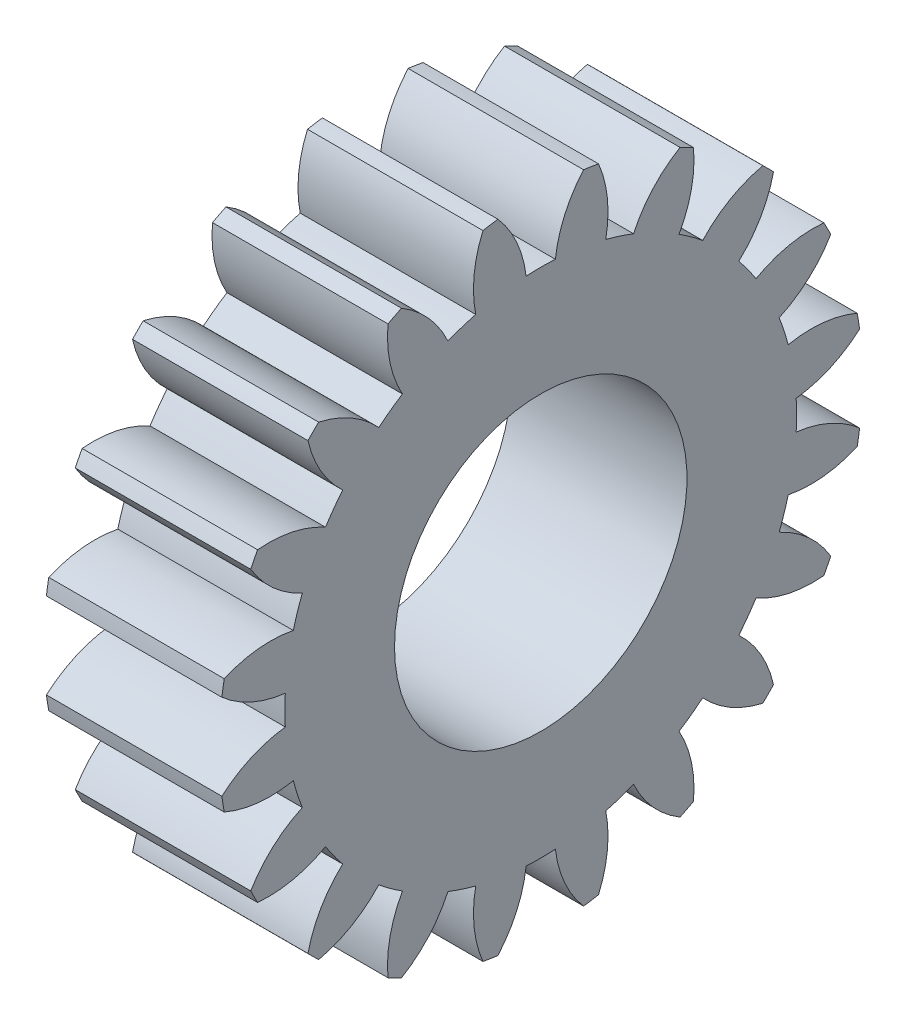
SolidWorks part; units mm, degrees
ref_plane "Plane1" through (0, 0, 0) normal (0, 0, 1) x (1, 0, 0)
ref_plane "Plane2" through (0, 0, 0) normal (0, 1, 0) x (1, 0, 0)
ref_plane "Plane3" through (0, 0, 0) normal (1, 0, 0) x (0, 0, -1)
sketch "HoldingSke" plane through (0, 0, 0) normal (0, 1, 0) x (1, 0, 0)
  line L0 (0, 0) -> (1.8794, -0.684)
  line L1 (-15, 0) -> (100, 0) construction
  line L2 (0, 0) -> (-2.1039, 2.3779)
  line L3 (0, 0) -> (-11.863, 4.5341)
  line L4 (0, 0) -> (8.1152, 2.9537)
  line L5 (0, 0) -> (-46.8476, -17.4728)
  line L6 (0, 0) -> (-2.4869, -1.6779)
  line L7 (-2.1039, 2.3779) -> (8.6586, 51.2059)
  line L8 (-76.2, 54.61) -> (-75.3, 54.61)
  line L9 (-71.009, 38.7566) -> (-53.1078, 45.2721)
  line L10 (-76.2, 71.12) -> (104.1128, 71.12)
  line L11 (0, 0) -> (-3, 0)
  line L12 (-76.2, 101.6) -> (-76.181, 101.6)
  line L13 (24.9733, 27.94) -> (52.9518, 28.4284)
  line L14 (24.9733, 27.94) -> (24.9743, 27.94)
  line L15 (24.9733, 27.94) -> (100.4006, 29.5858)
  line L16 (-63.627, -0.5) -> (-12.827, -0.5)
  circle A0 centre (0, 0) radius 2.5
  circle A1 centre (0, 0) radius 4.374
  circle A2 centre (0, 0) radius 37.5
  circle A3 centre (0, 0) radius 2.5
  dimension "MHD" = 8.748
  dimension "Hub_dia" = 75
  dimension "Bore" = 5
  dimension "MBD" = 5
  dimension "Num_teeth" = 20
  dimension "Pitch" = 2
  dimension "Overall_len" = 50
  dimension "Show_teeth" = 20
  dimension "Thickness" = 3
  dimension "OAL" = 50.0001
  dimension "T_dim" = 0.9
  dimension "Ap" = 20
  dimension "H" = 19.05
  dimension "Pitch_radius" = 180.3128
  dimension "Width" = 3
  dimension "Backlash" = 0.019
  dimension "Addendum_fac" = 1
  dimension "Dedendum_fac" = 1.25
  dimension "Clearance_fac" = 0.25
  dimension "Dedendum_add" = 0.001
  dimension "Module" = 0.5
sketch "BasProSke" plane through (0, 0, 0) normal (0, 1, 0) x (1, 0, 0)
  line L0 (-10, 0) -> (60, 0) construction
  line L1 (0, 0) -> (0, 5.5)
  line L2 (0, 0) -> (3, 0)
  line L3 (3, 0) -> (3, 5.5)
  line L4 (3, 5.5) -> (0, 5.5)
  dimension "Thickness" = 3
  dimension "Diameter" = 11
revolve "Base-Revolve" add sketch "BasProSke" angle 360 about L0
sketch "TooCutSke" plane through (0, 0, 0) normal (1, 0, 0) x (0, 0, -1)
  line L1 (0, 0) -> (0, 107) construction
  line L2 (0, 0) -> (-0.4255, 4.9819) construction
  line L3 (0, 0) -> (-1.5603, 9.8514) construction
  line L4 (-0.4255, 4.9819) -> (-0.7802, 4.9257) construction
  arc A0 (0.2499, 4.3669) -> (-0.2499, 4.3669) centre (0, 0) ccw
  arc A1 (0.7528, 5.4739) -> (-0.7528, 5.4739) centre (0, 0) ccw
  circle A2 centre (0, 0) radius 5 construction
  circle A3 centre (0, 0) radius 4.6985 construction
  arc A4 (-0.2499, 4.3669) -> (-0.7528, 5.4739) centre (-2.2361, 4.1322) ccw
  arc A5 (0.7528, 5.4739) -> (0.2499, 4.3669) centre (2.2361, 4.1322) ccw
  dimension "Root_dia" = 8.748
  dimension "Overcut_dia" = 11.0508
  dimension "Pitch_dia" = 10
  dimension "Base_dia" = 9.3969
  dimension "Flank_rad" = 2
  dimension "Half_ang" = 9
  dimension "Half_CT" = 0.359
extrude "ToothCut" cut sketch "TooCutSke" along normal through all
fillet "Breaks" [suppressed] radius 0.01
fillet "RootFillets" [suppressed] radius 0.126
pattern_circular "TeethCuts" count 20 every 18 about axis through (-10, 0, 0) along (1, 0, 0) of "ToothCut", "RootFillets", "Breaks"
sketch "HubNeaOneSke" plane through (0, 0, 0) normal (-1, 0, 0) x (0, 0, 1)
  circle A0 centre (0, 0) radius 4.374
  dimension "Diameter" = 8.748
extrude "HubNearOne" [suppressed] add sketch "HubNeaOneSke" along normal blind 47.0001
sketch "HubNeaBotSke" plane through (0, 0, 0) normal (-1, 0, 0) x (0, 0, 1)
  circle A0 centre (0, 0) radius 4.374
  dimension "Diameter" = 8.748
extrude "HubNearBoth" [suppressed] add sketch "HubNeaBotSke" along normal blind 23.5
ref_plane "FarPln" through (3, 0, 0) normal (1, 0, 0) x (0, 0, -1)
sketch "HubFarSke" plane through (3, 0, 0) normal (1, 0, 0) x (0, 0, -1)
  circle A0 centre (0, 0) radius 4.374
  dimension "Diameter" = 8.748
extrude "HubFar" [suppressed] add sketch "HubFarSke" along normal blind 23.5
sketch "BorSke" plane through (0, 0, 0) normal (1, 0, 0) x (0, 0, -1)
  circle A0 centre (0, 0) radius 2.5
  dimension "Diameter" = 5
extrude "Bore" cut sketch "BorSke" along normal mid plane 100.0001
sketch "KeySke" plane through (0, 0, 0) normal (1, 0, 0) x (0, 0, -1)
  line L0 (-1, 0) -> (-1, 3.4)
  line L1 (-1, 3.4) -> (1, 3.4)
  line L2 (1, 3.4) -> (1, 0)
  line L3 (0, 0) -> (0, 34) construction
  line L4 (-1, 0) -> (1, 0)
  dimension "Offset" = 3.4
  dimension "Width" = 2
extrude "Keyway" [suppressed] cut sketch "KeySke" along normal mid plane 100.0001
pattern_circular "Keyway2" [suppressed] count 2 every 90 about axis through (-10, 0, 0) along (1, 0, 0)
sketch "Croquis1" plane through (3, 0, 0) normal (1, 0, 0) x (0, 0, -1)
  line L0 (0, 2.5) -> (0, -2.5)
  line L1 (0, 0) -> (2.5, 0)
  circle A0 centre (0, 0) radius 2.5 construction
  circle A1 centre (0, 0) radius 5
  dimension "D1" = 10
equation "' \"Module@HoldingSke\" = 6.35"
equation "' \"Num_teeth@HoldingSke\" = 12"
equation "' \"Ap@HoldingSke\" =  20"
equation "' \"Ap@HoldingSke\" = 20"
equation "' \"Width@HoldingSke\" = 0.5 * 25.4"
equation "' \"Hub_dia@HoldingSke\"= 1 * 25.4"
equation "' \"Hub_dia@HoldingSke\" = 1 * 25.4"
equation "' \"Overall_len@HoldingSke\" = 1.0 * 25.4"
equation "' \"Bore@HoldingSke\" = 0.75 * 25.4"
equation "' \"T_dim@HoldingSke\" = 0.1 * 25.4"
equation "' \"Width@KeySke\" = 0.25 * 25.4"
equation "' \"Show_teeth@HoldingSke\" = 13"
equation "' \"Backlash@HoldingSke\" = 0.009 * 25.4"
equation "' \"Addendum_fac@HoldingSke\" = 1.0"
equation "' \"Dedendum_fac@HoldingSke\" = 1.25"
equation "' \"Dedendum_add@HoldingSke\" = 0.00005 * 25.4"
equation "' \"Clearance_fac@HoldingSke\" = 0.25"
equation "\"Pitch@HoldingSke\" = 1 / \"Module@HoldingSke\""
equation "\"Overcut_dia@TooCutSke\" = (\"Num_teeth@HoldingSke\" + 2 * \"Addendum_fac@HoldingSke\") / \"Pitch@HoldingSke\" + 0.002 * 25.4"
equation "\"Pitch_dia@TooCutSke\" = \"Num_teeth@HoldingSke\" / \"Pitch@HoldingSke\""
equation "\"Base_dia@TooCutSke\" = \"Num_teeth@HoldingSke\" / \"Pitch@HoldingSke\" * cos((\"Ap@HoldingSke\"  * 3.14159265 / 180))"
equation "\"Root_dia@TooCutSke\" = (\"Num_teeth@HoldingSke\" + 2) / \"Pitch@HoldingSke\" - 2 * (\"Addendum_fac@HoldingSke\" + \"Dedendum_fac@HoldingSke\") / \"Pitch@HoldingSke\" - \"Dedendum_add@HoldingSke\" * 2"
equation "\"Half_ang@TooCutSke\" = 180 / \"Num_teeth@HoldingSke\""
equation "\"Half_CT@TooCutSke\" = \"Num_teeth@HoldingSke\" / \"Pitch@HoldingSke\" * sin((3.14159265 / 2 / \"Num_teeth@HoldingSke\")) / 2 - 7 * \"Backlash@HoldingSke\" / 4"
equation "\"Flank_rad@TooCutSke\" = \"Num_teeth@HoldingSke\" / \"Pitch@HoldingSke\" / 5"
equation "\"Radius@RootFillets\" = \"Clearance_fac@HoldingSke\" / \"Pitch@HoldingSke\" + \"Dedendum_add@HoldingSke\""
equation "\"Break_rad@Breaks\" = 0.02 / \"Pitch@HoldingSke\""
equation "\"Thickness@HoldingSke\" = \"Width@HoldingSke\""
equation "\"OAL@HoldingSke\" = \"Thickness@HoldingSke\""
equation "\"MHD@HoldingSke\" = (\"Num_teeth@HoldingSke\" + 2) / \"Pitch@HoldingSke\" - 2 * (\"Addendum_fac@HoldingSke\" + \"Dedendum_fac@HoldingSke\")  / \"Pitch@HoldingSke\" - \"Dedendum_add@HoldingSke\" * 2"
equation "\"MBD@HoldingSke\" = (\"Num_teeth@HoldingSke\" + 2) / \"Pitch@HoldingSke\" - 2 * (\"Addendum_fac@HoldingSke\" + \"Dedendum_fac@HoldingSke\")  / \"Pitch@HoldingSke\" - \"Dedendum_add@HoldingSke\" * 2 - 0.002 * 25.4"
equation "\"MHD@HoldingSke\" = ((sgn( \"MHD@HoldingSke\" - \"Hub_dia@HoldingSke\" )-1)*( \"MHD@HoldingSke\" - \"Hub_dia@HoldingSke\" ))/-2+ \"Hub_dia@HoldingSke\""
equation "\"MBD@HoldingSke\" = ((sgn( \"MBD@HoldingSke\" - \"Bore@HoldingSke\" )-1)*( \"MBD@HoldingSke\" - \"Bore@HoldingSke\" ))/-2+ \"Bore@HoldingSke\""
equation "\"OAL@HoldingSke\" = ((sgn( \"OAL@HoldingSke\" - \"Overall_len@HoldingSke\" )+1)*( \"OAL@HoldingSke\" - \"Overall_len@HoldingSke\" ))/2 + \"Overall_len@HoldingSke\" + 0.000002 * 25.4"
equation "\"Num_teeth@TeethCuts\" = int( \"Show_teeth@HoldingSke\" ) + 1"
equation "\"Num_teeth@TeethCuts\" = ((sgn( \"Num_teeth@TeethCuts\" - \"Num_teeth@HoldingSke\" )-1)*( \"Num_teeth@TeethCuts\" - \"Num_teeth@HoldingSke\" ))/-2+ \"Num_teeth@HoldingSke\""
equation "\"Num_teeth@TeethCuts\" = ((sgn( \"Num_teeth@TeethCuts\" - 2.0)+1)*( \"Num_teeth@TeethCuts\" - 2.0))/2 +2.0"
equation "\"Angle@TeethCuts\" = 360.0 / \"Num_teeth@HoldingSke\""
equation "\"Diameter@BasProSke\" = (\"Num_teeth@HoldingSke\" + 2 * \"Addendum_fac@HoldingSke\") / \"Pitch@HoldingSke\""
equation "\"Thickness@BasProSke\"  = \"Thickness@HoldingSke\""
equation "' \"Fillet_rad@BasProSke\" =  \"Thickness@HoldingSke\" * 0.05"
equation "' \"Fillet_rad@BasProSke\" = \"Thickness@HoldingSke\" * 0.05"
equation "\"MHD@HoldingSke\" = ((sgn( \"MHD@HoldingSke\" - \"Root_dia@TooCutSke\" )-1)*( \"MHD@HoldingSke\" - \"Root_dia@TooCutSke\" ))/-2+ \"Root_dia@TooCutSke\""
equation "\"Diameter@HubNeaOneSke\" = \"MHD@HoldingSke\""
equation "\"Length@HubNearOne\" = \"OAL@HoldingSke\" - \"Thickness@BasProSke\""
equation "\"Diameter@HubNeaBotSke\" = \"MHD@HoldingSke\""
equation "\"Length@HubNearBoth\" = ( \"OAL@HoldingSke\" - \"Thickness@BasProSke\" ) / 2.0"
equation "\"Thickness@FarPln\" = \"Thickness@BasProSke\""
equation "\"Diameter@HubFarSke\" = \"MHD@HoldingSke\""
equation "\"Length@HubFar\" = ( \"OAL@HoldingSke\" - \"Thickness@BasProSke\" ) / 2.0"
equation "\"Diameter@BorSke\" = \"MBD@HoldingSke\""
equation "\"D1@Bore\" = \"OAL@HoldingSke\" * 2.0"
equation "\"D1@Keyway\" = \"OAL@HoldingSke\" * 2.0"
equation "\"Offset@KeySke\" = \"T_dim@HoldingSke\" + \"MBD@HoldingSke\" / 2.0"
